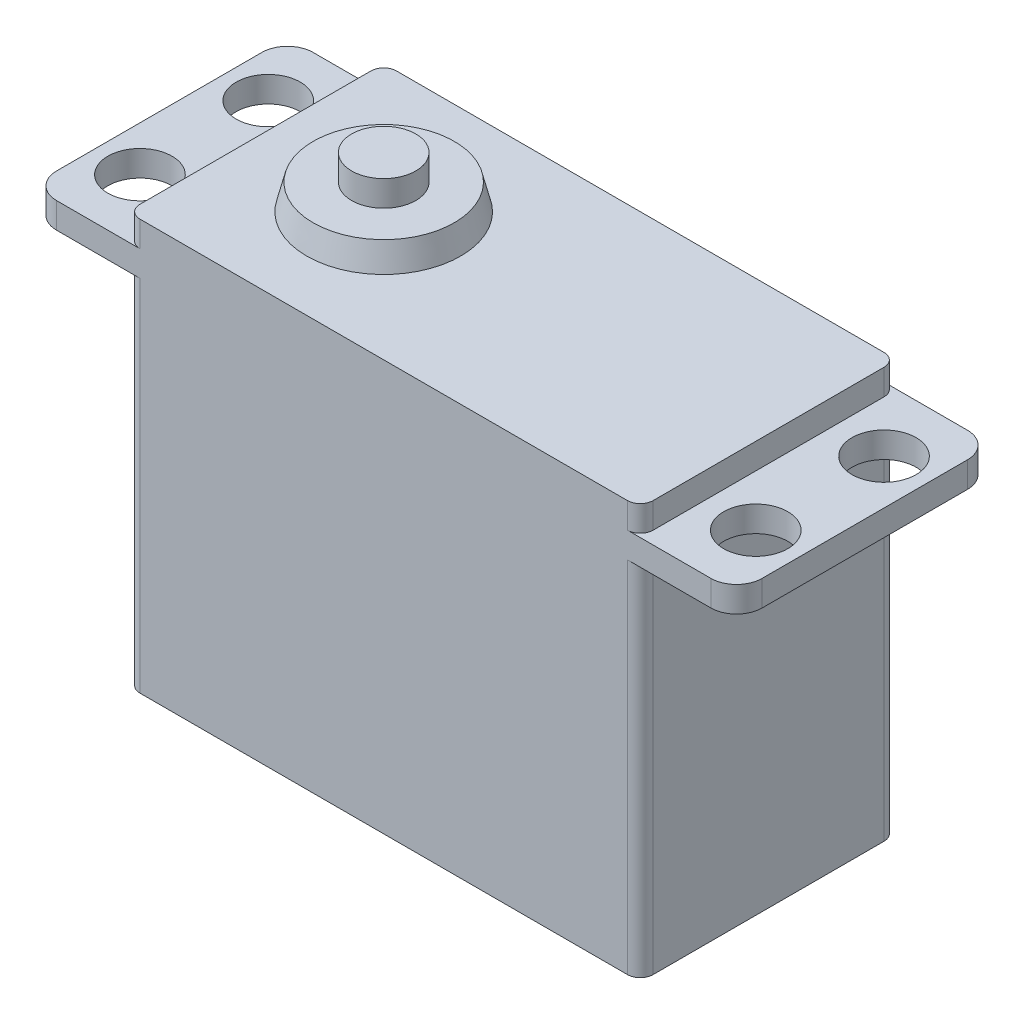
SolidWorks part; units mm, degrees
ref_plane "Front Plane" through (0, 0, 0) normal (0, 0, 1) x (1, 0, 0)
ref_plane "Top Plane" through (0, 0, 0) normal (0, 1, 0) x (1, 0, 0)
ref_plane "Right Plane" through (0, 0, 0) normal (1, 0, 0) x (0, 0, -1)
sketch "Sketch1" plane through (0, 0, 0) normal (0, 1, 0) x (1, 0, 0)
  line L1 (0, 0) -> (55, 0)
  line L2 (0, 0) -> (0, 20)
  line L3 (0, 20) -> (55, 20)
  line L4 (55, 0) -> (55, 20)
  circle A0 centre (3.5, 15) radius 2.5
  circle A1 centre (3.5, 5) radius 2.5
  circle A2 centre (51.5, 15) radius 2.5
  circle A3 centre (51.5, 5) radius 2.5
  dimension "D3" = 5
  dimension "D4" = 10
  dimension "D5" = 5
  dimension "D6" = 3.5
  dimension "D7" = 3.5
  dimension "D1" = 55
  dimension "D2" = 20
extrude "Boss-Extrude1" add sketch "Sketch1" along normal blind 2
fillet "Fillet1" radius 2 4 edges at (55, 1, -20) (55, 1, 0) (0, 1, 0) (0, 1, -20)
sketch "Sketch2" plane through (0, 0, 0) normal (0, -1, 0) x (1, 0, 0)
  line L0 (2, 0) -> (53, 0) construction
  line L1 (7.5, 0) -> (47.5, 0)
  line L2 (7.5, 0) -> (7.5, -20)
  line L3 (7.5, -20) -> (47.5, -20)
  line L4 (47.5, 0) -> (47.5, -20)
  line L5 (53, -20) -> (2, -20) construction
  line L6 (0, -18) -> (0, -2) construction
  dimension "D1" = 40
  dimension "D2" = 7.5
extrude "Boss-Extrude2" add sketch "Sketch2" along normal blind 28
sketch "Sketch3" plane through (0, 2, 0) normal (0, 1, 0) x (1, 0, 0)
  line L0 (53, 20) -> (2, 20) construction
  line L1 (7.5, 20) -> (47.5, 20)
  line L2 (7.5, 20) -> (7.5, 0)
  line L3 (7.5, 0) -> (47.5, 0)
  line L4 (47.5, 20) -> (47.5, 0)
  line L5 (2, 0) -> (53, 0) construction
  line L6 (0, 18) -> (0, 2) construction
  dimension "D1" = 40
  dimension "D2" = 7.5
extrude "Boss-Extrude3" add sketch "Sketch3" along normal blind 2
fillet "Fillet2" radius 1 8 edges at (47.5, -14, -20) (7.5, -14, -20) (47.5, -14, 0) (7.5, -14, 0) (47.5, 3, -20) (47.5, 3, 0) (7.5, 3, -20) (7.5, 3, 0)
ref_plane "Plane1" through (0, 0, -10) normal (0, 0, 1) x (1, 0, 0)
sketch "Sketch4" plane through (0, 0, -10) normal (0, 0, 1) x (1, 0, 0)
  line L0 (17.5, 4) -> (11.5, 4)
  line L1 (8.5, 4) -> (46.5, 4) construction
  line L2 (11.5, 4) -> (12, 6)
  line L3 (12, 6) -> (15, 6)
  line L4 (15, 6) -> (15, 8)
  line L5 (15, 8) -> (17.5, 8)
  line L6 (17.5, 8) -> (17.5, 4)
  line L8 (7.5, 2) -> (7.5, 4) construction
  dimension "D1" = 4
  dimension "D2" = 6
  dimension "D3" = 2.5
  dimension "D4" = 2
  dimension "D5" = 3
  dimension "D6" = 10
revolve "Revolve1" add sketch "Sketch4" angle 360 about L6
